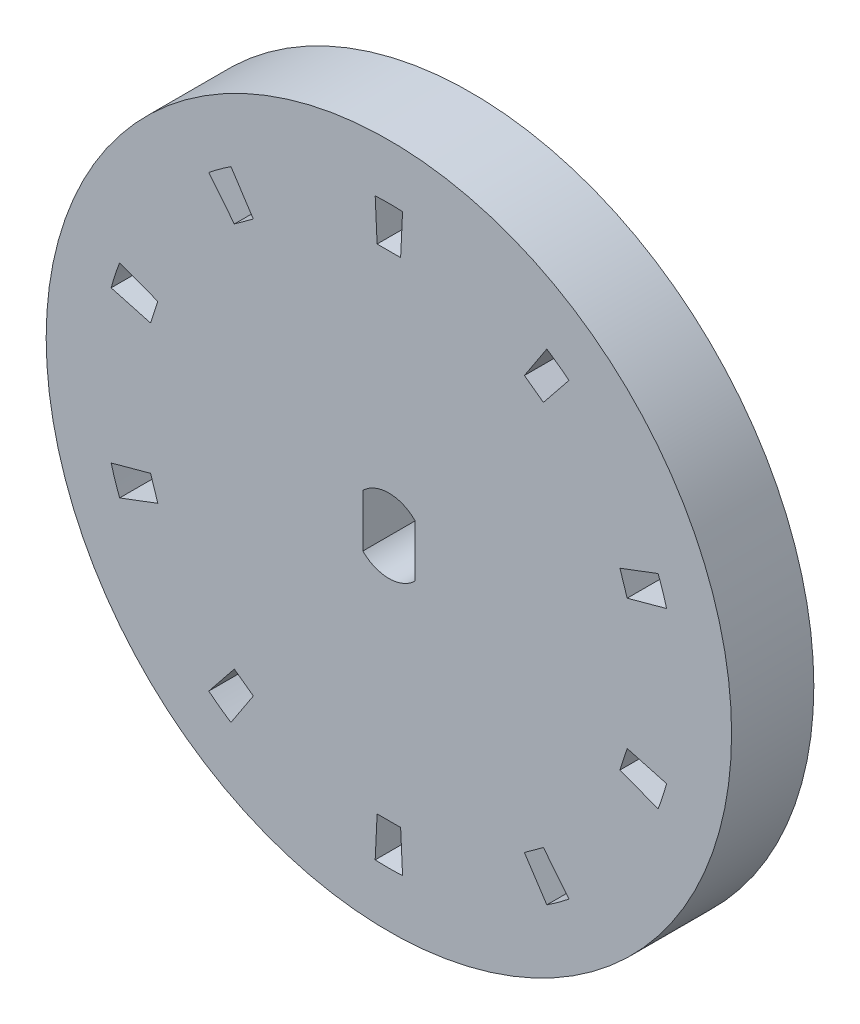
SolidWorks part; units mm, degrees
ref_plane "Front Plane" through (0, 0, 0) normal (0, 0, 1) x (1, 0, 0)
ref_plane "Top Plane" through (0, 0, 0) normal (0, 1, 0) x (1, 0, 0)
ref_plane "Right Plane" through (0, 0, 0) normal (1, 0, 0) x (0, 0, -1)
sketch "Sketch2" plane through (0, 0, 0) normal (0, 0, 1) x (1, 0, 0)
  line L2 (1.9, -1.9183) -> (1.9, 1.9183)
  line L4 (-1.9, -1.9183) -> (-1.9, 1.9183)
  line L5 (1.452, -2.2764) -> (-1.452, 2.2764) construction
  line L6 (1.452, 2.2764) -> (-1.452, -2.2764) construction
  circle A0 centre (0, 0) radius 25
  arc A1 (-1.9, -1.9183) -> (1.9, -1.9183) centre (0, 0) ccw
  circle A2 centre (0, 0) radius 1
  arc A3 (1.9, 1.9183) -> (-1.9, 1.9183) centre (0, 0) ccw
  dimension "D1" = 50
  dimension "D2" = 5.4
  dimension "D3" = 2
  dimension "D4" = 3.8
  dimension "D5" = 1.9
extrude "Boss-Extrude1" add sketch "Sketch2" against normal blind 4 contours A0 | L2 A3 L4 A1
sketch "Sketch3" plane through (0, 0, -4) normal (0, 0, -1) x (-1, 0, 0)
  circle A0 centre (0, 0) radius 25 construction
  circle A1 centre (0, 0) radius 1 construction
  circle A2 centre (0, 0) radius 25
  circle A3 centre (0, 0) radius 1
extrude "Boss-Extrude2" add sketch "Sketch3" along normal blind 2
sketch "Sketch4" plane through (0, 0, 0) normal (0, 0, 1) x (1, 0, 0)
  line L0 (0, 0) -> (0, 27.7) construction
  line L1 (0, 0) -> (0.9989, 20.9762) construction
  line L2 (0, 0) -> (-0.9989, 20.9762) construction
  line L4 (-0.8571, 18) -> (0.8571, 18)
  line L5 (0.9989, 20.9762) -> (0.8571, 18)
  line L7 (-0.8571, 18) -> (-0.9989, 20.9762)
  arc A0 (0.9989, 20.9762) -> (-0.9989, 20.9762) centre (0, 0) ccw
  dimension "D1" = 42
extrude "Cut-Extrude1" cut sketch "Sketch4" against normal through all both and the other way through all
sketch "Sketch5" plane through (0, 0, 0) normal (0, 1, 0) x (1, 0, 0)
  line L0 (0, -11.3819) -> (0, 14.3035) construction
pattern_circular "CirPattern1" count 10 over 360 about axis through (0, 0, 0) along (0, 0, 1) of "Cut-Extrude1"
